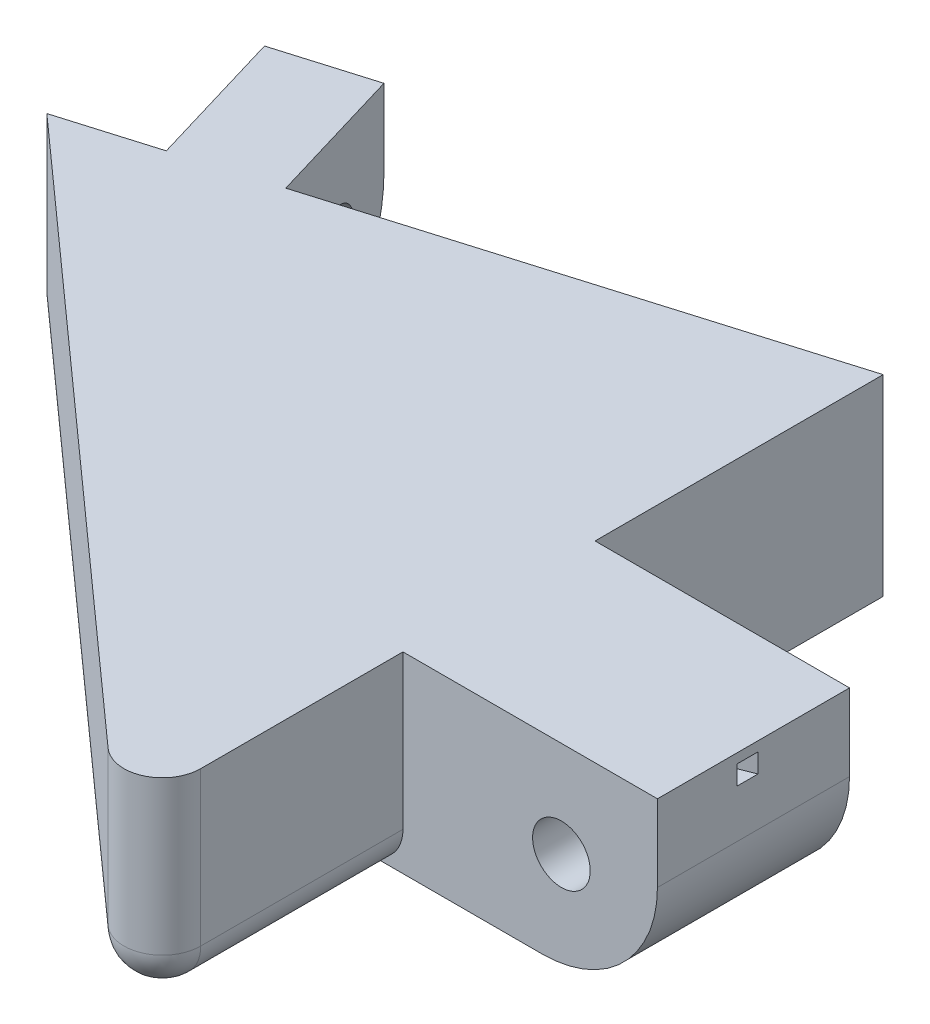
SolidWorks part; units mm, degrees
ref_plane "Front Plane" through (0, 0, 0) normal (0, 0, 1) x (1, 0, 0)
ref_plane "Top Plane" through (0, 0, 0) normal (0, 1, 0) x (1, 0, 0)
ref_plane "Right Plane" through (0, 0, 0) normal (1, 0, 0) x (0, 0, -1)
sketch "Sketch1" plane through (0, 0, 0) normal (0, 1, 0) x (1, 0, 0)
  line L0 (0, 22.1643) -> (0, -28.6357)
  line L1 (0, -28.6357) -> (-42.5971, 9.4643)
  line L2 (-42.5971, 9.4643) -> (0, 22.1643)
  line L4 (0, 3.1143) -> (16.8255, 3.1143)
  line L5 (0, 3.1143) -> (0, -9.5857)
  line L6 (0, -9.5857) -> (16.8255, -9.5857)
  line L7 (16.8255, 3.1143) -> (16.8255, -9.5857)
  point P8 (0, 0)
  dimension "D1" = 50.8
  dimension "D2" = 57.15
  dimension "D3" = 44.45
  dimension "D4" = 12.7
  dimension "D5" = 19.05
extrude "Boss-Extrude1" add sketch "Sketch1" along normal blind 12.7 contours L2 L1 L0 | L7 L4 L0 L6
fillet "Fillet1" radius 7.62 1 edges at (16.8255, 0, 3.2357)
sketch "Sketch2" plane through (0, 0, 9.5857) normal (0, 0, 1) x (1, 0, 0)
  line L0 (0, 12.7) -> (16.8255, 12.7) construction
  circle A0 centre (10.4755, 6.35) radius 1.905
  dimension "D1" = 3.81
  dimension "D2" = 6.35
  dimension "D3" = 6.35
extrude "Cut-Extrude1" cut sketch "Sketch2" against normal blind 12.7
sketch "Sketch3" plane through (-6.0687, 0, -20.355) normal (-0.2857, 0, -0.9583) x (-0.9583, 0, 0.2857)
  line L0 (38.1173, 12.7) -> (-6.3327, 12.7) construction
  line L1 (31.7673, 12.7) -> (25.4173, 12.7)
  line L2 (31.7673, 12.7) -> (31.7673, 0)
  line L3 (31.7673, 0) -> (25.4173, 0)
  line L4 (25.4173, 12.7) -> (25.4173, 0)
  line L5 (38.1173, 0) -> (-6.3327, 0) construction
  line L6 (38.1173, 12.7) -> (38.1173, 0) construction
  dimension "D1" = 6.35
  dimension "D2" = 6.35
extrude "Boss-Extrude2" add sketch "Sketch3" along normal blind 9.652
fillet "Fillet2" radius 7.62 1 edges at (-36.2269, 0, -21.4354)
sketch "Sketch4" plane through (-30.4431, 0, 9.0764) normal (-0.9583, 0, 0.2857) x (0.2857, 0, 0.9583)
  line L0 (-30.8924, 12.7) -> (-21.2404, 12.7) construction
  line L1 (-21.2404, 12.7) -> (-21.2404, 0) construction
  circle A0 centre (-26.0664, 6.604) radius 1.905
  dimension "D1" = 3.81
  dimension "D2" = 6.096
  dimension "D3" = 4.826
extrude "Cut-Extrude2" cut sketch "Sketch4" against normal blind 12.7
fillet "Fillet3" radius 2.54 1 edges at (0, 6.35, 28.6357)
sketch "Sketch5" plane through (-8.8264, 0, -29.6047) normal (-0.2857, 0, -0.9583) x (-0.9583, 0, 0.2857)
  line L0 (31.7673, 12.7) -> (25.4173, 12.7) construction
  line L1 (27.9573, 10.795) -> (29.2273, 10.795)
  line L2 (27.9573, 10.795) -> (27.9573, 12.065)
  line L3 (27.9573, 12.065) -> (29.2273, 12.065)
  line L4 (29.2273, 10.795) -> (29.2273, 12.065)
  line L5 (27.9573, 10.795) -> (29.2273, 12.065) construction
  line L6 (27.9573, 12.065) -> (29.2273, 10.795) construction
  line L7 (27.9573, 0.635) -> (29.2273, 0.635)
  line L8 (27.9573, 0.635) -> (27.9573, 1.905)
  line L9 (27.9573, 1.905) -> (29.2273, 1.905)
  line L10 (29.2273, 0.635) -> (29.2273, 1.905)
  line L11 (27.9573, 0.635) -> (29.2273, 1.905) construction
  line L12 (27.9573, 1.905) -> (29.2273, 0.635) construction
  line L13 (31.7673, 0) -> (25.4173, 0) construction
  line L14 (25.4173, 7.62) -> (25.4173, 0) construction
  line L15 (25.4173, 12.7) -> (25.4173, 0) construction
  line L16 (-14.816, 18.0504) -> (-14.816, -7.6489) construction
  line L17 (-7.1103, 18.0504) -> (-7.1103, -11.2938) construction
  line L18 (-10.8152, 18.0504) -> (-10.8152, -8.5756) construction
  point P0 (28.5923, 11.43)
  point P5 (28.5923, 1.27)
  point P12 (28.5923, 12.7)
  dimension "D1" = 1.27
  dimension "D2" = 1.27
  dimension "D3" = 1.27
  dimension "D4" = 1.27
  dimension "D5" = 1.27
  dimension "D6" = 1.27
  dimension "D7" = 3.175
  dimension "D8" = 3.175
revolve "Cut-Revolve1" cut sketch "Sketch5" angle 360 about L18
fillet "Fillet4" radius 2.54 3 edges at (0, 0, 16.2709) (-23.4152, 0, 7.6925) (-1.503, 0, 25.2747)
